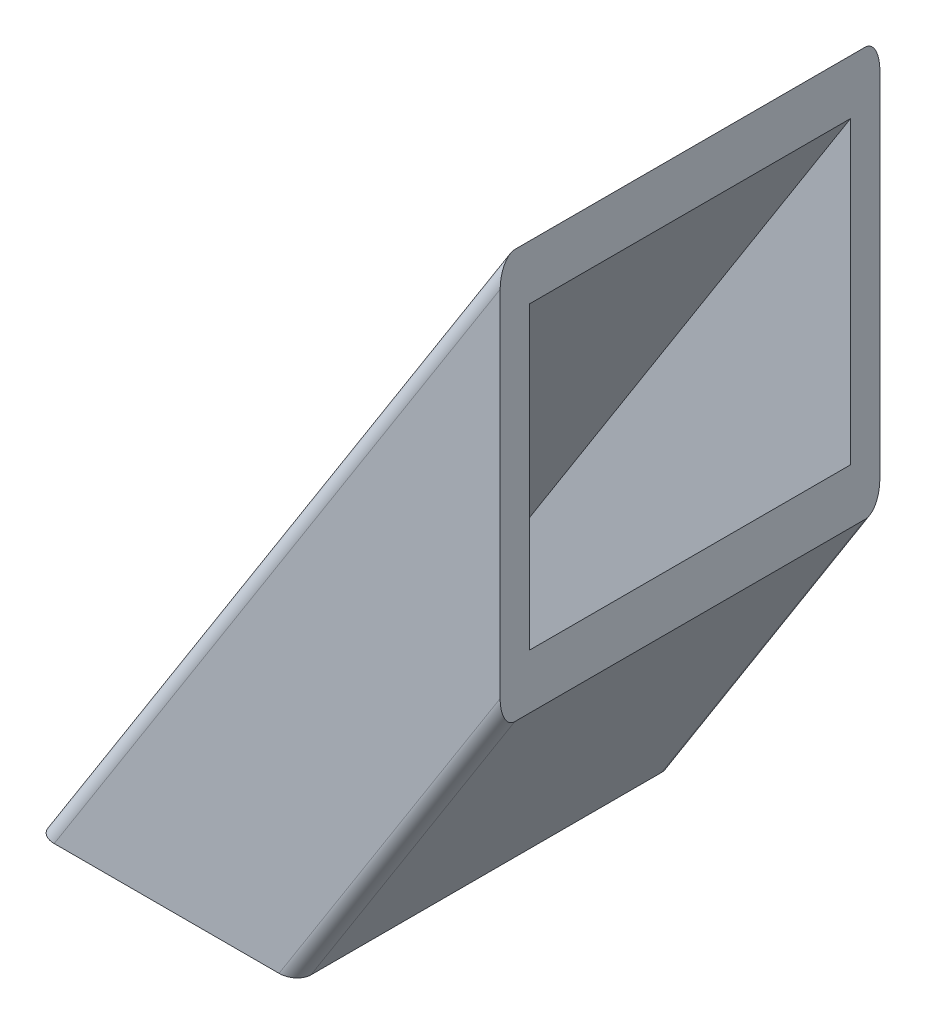
SolidWorks part; units mm, degrees
ref_plane "Front Plane" through (0, 0, 0) normal (0, 0, 1) x (1, 0, 0)
ref_plane "Top Plane" through (0, 0, 0) normal (0, 1, 0) x (1, 0, 0)
ref_plane "Right Plane" through (0, 0, 0) normal (1, 0, 0) x (0, 0, -1)
sketch "Sketch1" plane through (0, 0, 0) normal (0, 0, 1) x (1, 0, 0)
  line L0 (0, 0) -> (-17.7641, 0)
  line L1 (13.9575, 50) -> (13.9575, 22)
  line L2 (0, 0) -> (13.9575, 22)
  line L3 (-17.7641, 0) -> (13.9575, 50)
  line L5 (14.3, 0) -> (-14.3, 0) construction
  dimension "D1" = 50
  dimension "D2" = 15
  dimension "D4" = 28
extrude "Boss-Extrude1" add sketch "Sketch1" along normal blind 26
shell "Shell1" thickness 2
sketch "Sketch2" plane through (0, 2, 0) normal (0, 1, 0) x (1, 0, 0)
  line L0 (-1.0997, -2) -> (-1.0997, -24)
  line L1 (-1.0997, -24) -> (-14.1267, -24)
  line L2 (-14.1267, -24) -> (-14.1267, -2)
  line L3 (-14.1267, -2) -> (-1.0997, -2)
extrude "Cut-Extrude1" cut sketch "Sketch2" against normal up to next
fillet "Fillet1" radius 1 4 edges at (6.9788, 11, 0) (-1.9033, 25, 0) (6.9788, 11, 26) (-1.9033, 25, 26)
